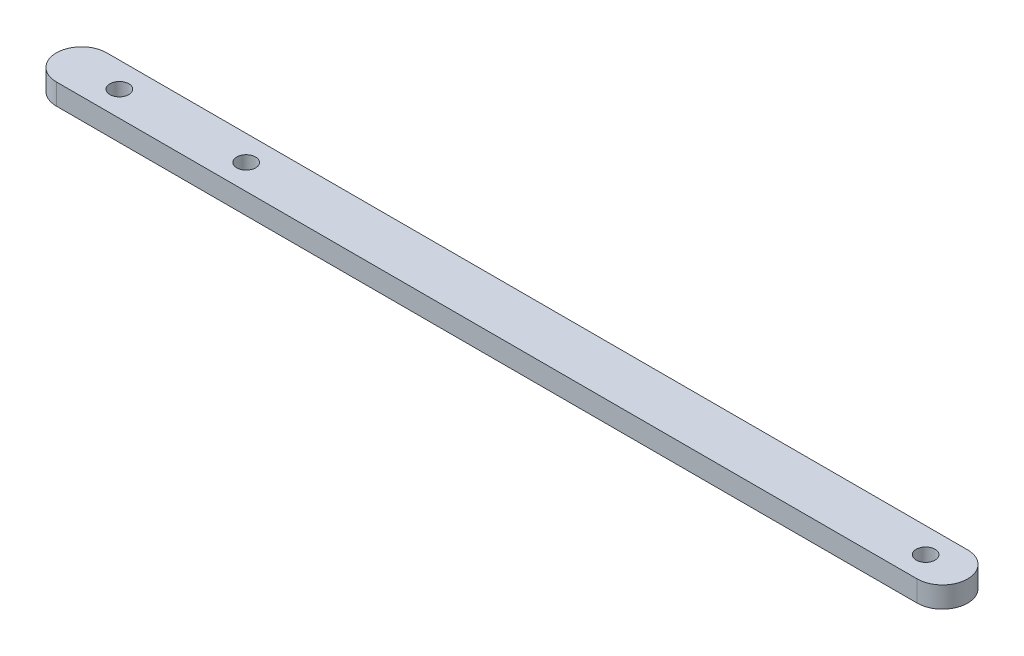
SolidWorks part; units mm, degrees
ref_plane "Front Plane" through (0, 0, 0) normal (0, 0, 1) x (1, 0, 0)
ref_plane "Top Plane" through (0, 0, 0) normal (0, 1, 0) x (1, 0, 0)
ref_plane "Right Plane" through (0, 0, 0) normal (1, 0, 0) x (0, 0, -1)
sketch "Sketch1" plane through (0, 0, 0) normal (0, 1, 0) x (1, 0, 0)
  line L0 (-43.6384, 0) -> (161.3616, 0) construction
  line L1 (-43.6384, 6) -> (161.3616, 6)
  line L2 (-43.6384, -6) -> (161.3616, -6)
  arc A0 (-43.6384, 6) -> (-43.6384, -6) centre (-43.6384, 0) ccw
  arc A1 (161.3616, -6) -> (161.3616, 6) centre (161.3616, 0) ccw
  point P3 (58.8616, 0)
  dimension "D1" = 12
  dimension "D2" = 205
extrude "Boss-Extrude1" add sketch "Sketch1" along normal blind 5
sketch "Sketch2" plane through (0, 5, 0) normal (0, 1, 0) x (1, 0, 0)
  line L0 (0, 0) -> (-72.2424, 0) construction
  line L1 (0, 0) -> (196.2662, 0) construction
  line L2 (-49.6384, 0) -> (-49.6384, 24.9678) construction
  line L3 (-49.6384, 24.9678) -> (-72.2424, 6.5664) construction
  line L4 (167.3616, 0) -> (167.3616, 31.4885) construction
  circle A1 centre (-4.4384, 0) radius 2.25
  circle A2 centre (157.3616, 0) radius 2.25
  arc A3 (-43.6384, 6) -> (-43.6384, -6) centre (-43.6384, 0) ccw construction
  arc A4 (161.3616, -6) -> (161.3616, 6) centre (161.3616, 0) ccw construction
  circle A5 centre (-34.6384, 0) radius 2.25
  dimension "D1" = 4.5
  dimension "D4" = 15
  dimension "D2" = 4.5
  dimension "D3" = 10
  dimension "D5" = 30.2
extrude "Cut-Extrude1" cut sketch "Sketch2" against normal blind 8
